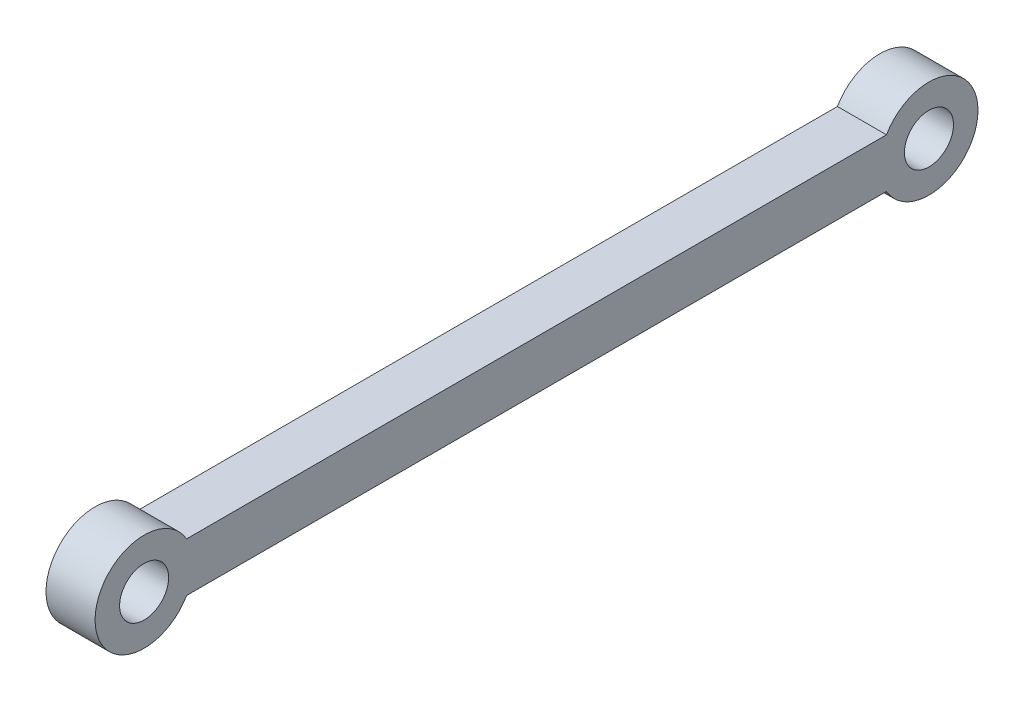
SolidWorks part; units mm, degrees
ref_plane "정면" through (0, 0, 0) normal (0, 0, 1) x (1, 0, 0)
ref_plane "윗면" through (0, 0, 0) normal (0, 1, 0) x (1, 0, 0)
ref_plane "우측면" through (0, 0, 0) normal (1, 0, 0) x (0, 0, -1)
sketch "스케치1" plane through (0, 0, 0) normal (1, 0, 0) x (0, 0, -1)
  line L0 (-20, 0) -> (20, 0) construction
  line L1 (-17.8349, 1.25) -> (17.8349, 1.25)
  line L3 (-17.8349, -1.25) -> (17.8349, -1.25)
  line L5 (0, 1.25) -> (0, -1.25) construction
  arc A0 (-17.8349, 1.25) -> (-17.8349, -1.25) centre (-20, 0) ccw
  circle A1 centre (-20, 0) radius 1.25
  arc A2 (17.8349, -1.25) -> (17.8349, 1.25) centre (20, 0) ccw
  circle A3 centre (20, 0) radius 1.25
  dimension "D3" = 5
  dimension "D4" = 5
  dimension "D1" = 2.5
  dimension "D2" = 40
extrude "보스-돌출1" add sketch "스케치1" along normal blind 2.5
equation "\"link11\" = 80"
equation "\"link12\" = 40"
equation "\"link21\"= 60"
equation "\"link22\"= 40"
equation "\"link31\"= 50"
equation "\"link32\"= 40"
equation "\"link41\"= 40"
equation "\"link42\"= 40"
equation "\"D2@스케치1\"=\"link42\""
